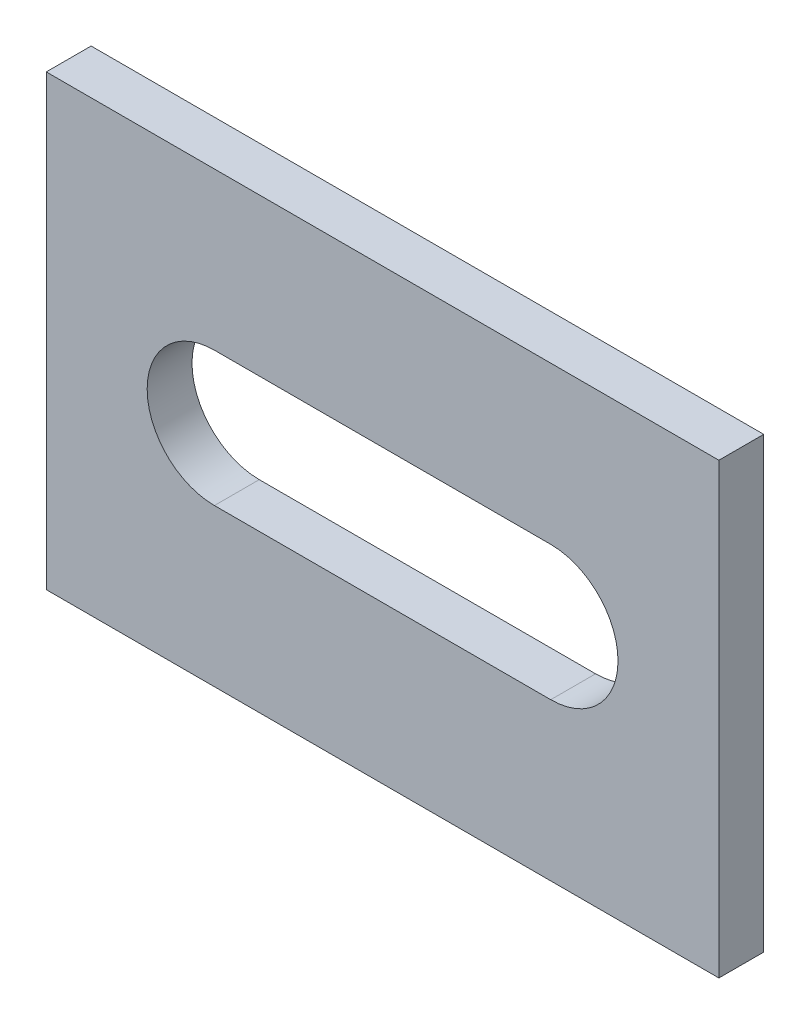
SolidWorks part; units mm, degrees
ref_plane "正面" through (0, 0, 0) normal (0, 0, 1) x (1, 0, 0)
ref_plane "平面" through (0, 0, 0) normal (0, 1, 0) x (1, 0, 0)
ref_plane "右側面" through (0, 0, 0) normal (1, 0, 0) x (0, 0, -1)
sketch "ｽｹｯﾁ1" plane through (0, 0, 0) normal (0, 0, 1) x (1, 0, 0)
  line L0 (-7.5, 0) -> (7.5, 0) construction
  line L1 (-15, 10) -> (15, 10)
  line L2 (-15, 10) -> (-15, -10)
  line L3 (-15, -10) -> (15, -10)
  line L4 (15, 10) -> (15, -10)
  line L5 (-15, 10) -> (15, -10) construction
  line L6 (-15, -10) -> (15, 10) construction
  line L7 (-7.5, 3) -> (7.5, 3)
  line L8 (-7.5, -3) -> (7.5, -3)
  arc A0 (-7.5, 3) -> (-7.5, -3) centre (-7.5, 0) ccw
  arc A1 (7.5, -3) -> (7.5, 3) centre (7.5, 0) ccw
  point P0 (0, 0)
  point P8 (0, 0)
  dimension "D1" = 30
  dimension "D2" = 20
  dimension "D3" = 6
  dimension "D4" = 15
  dimension "D5" = 7.5
extrude "ﾎﾞｽ - 押し出し1" add sketch "ｽｹｯﾁ1" along normal blind 2
